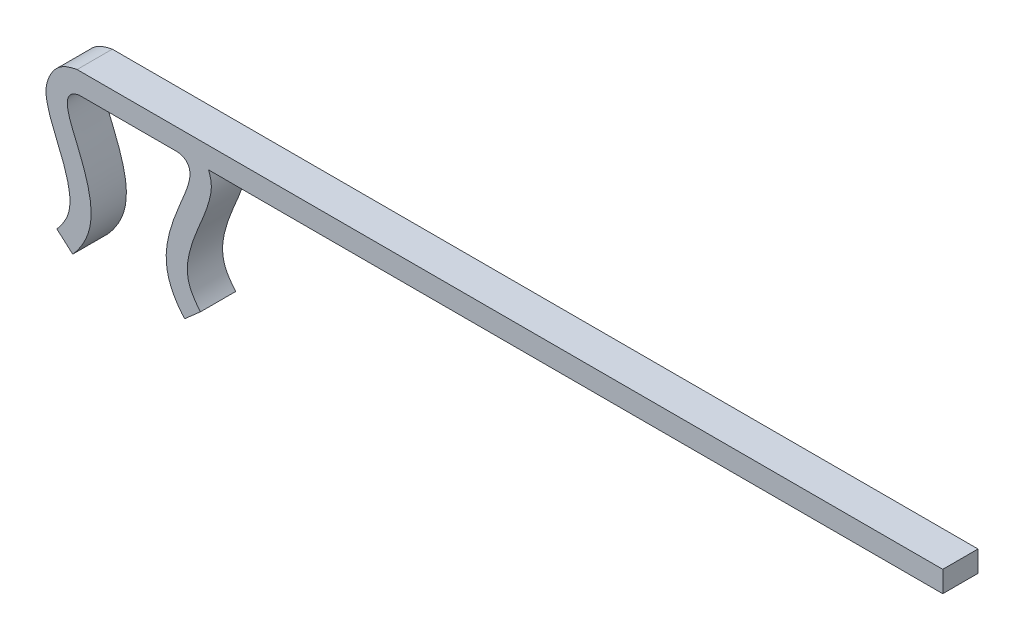
SolidWorks part; units mm, degrees
ref_plane "Front Plane" through (0, 0, 0) normal (0, 0, 1) x (1, 0, 0)
ref_plane "Top Plane" through (0, 0, 0) normal (0, 1, 0) x (1, 0, 0)
ref_plane "Right Plane" through (0, 0, 0) normal (1, 0, 0) x (0, 0, -1)
sketch "Sketch1" plane through (0, 0, 0) normal (0, 0, 1) x (1, 0, 0)
  line L0 (-3.0978, 0) -> (-0.55, 0) construction
  line L1 (-0.55, 2) -> (-0.7041, 2)
  line L2 (0, 2.8494) -> (0, -0.1797) construction
  line L3 (-0.55, 2) -> (0.55, 2)
  line L4 (0.7934, 0) -> (1.0189, 0.1979)
  line L5 (-0.55, -2) -> (0.55, -2)
  line L7 (0.55, 2) -> (0.7041, 2)
  line L8 (0.55, 2.3) -> (11.55, 2.3)
  line L9 (-0.55, 2.3) -> (-0.7319, 2.3)
  line L10 (-0.55, 2.3) -> (0.55, 2.3)
  line L11 (-0.7934, 0) -> (-1.0189, 0.1979)
  line L12 (1.133, 2) -> (11.55, 2)
  line L13 (11.55, 2.3) -> (11.55, 2)
  spline S0 degree 3 poles (-0.7041, 2) (-0.9849, 1.9476) (-0.6535, 1.2461) (-0.4405, 0.581) (-0.6577, 0.1546) (-0.7934, 0) knots 0 0 0 0 0.316391 0.760408 1 1 1 1
  spline S1 degree 1 poles (-0.7319, 2.3) (-1.0189, 0.1979) knots 0 0 1 1 construction
  spline S2 degree 3 poles (-0.7319, 2.3) (-0.7497, 2.2967) (-0.779, 2.2922) (-0.887, 2.2619) (-1.0567, 2.1715) (-1.1959, 1.8955) (-1.157, 1.6609) (-1.0749, 1.4074) (-0.9572, 1.1539) (-0.8699, 0.8996) (-0.8276, 0.6932) (-0.8349, 0.5301) (-0.8775, 0.3872) (-0.9707, 0.2527) (-1.0189, 0.1979) knots -0.010245 -0.010245 -0.010245 -0.010245 0.00554 0.021325 0.052895 0.116035 0.179176 0.242316 0.368597 0.494877 0.621158 0.747439 0.873719 1 1 1 1
  spline S3 degree 3 poles (1.133, 2) (1.1455, 1.9701) (1.1869, 1.841) (1.157, 1.6609) (1.0749, 1.4074) (0.9572, 1.1539) (0.8699, 0.8996) (0.8276, 0.6932) (0.8349, 0.5301) (0.8775, 0.3872) (0.9707, 0.2527) (1.0189, 0.1979) knots 0.096954 0.096954 0.096954 0.096954 0.116035 0.179176 0.242316 0.368597 0.494877 0.621158 0.747439 0.873719 1 1 1 1
  spline S4 degree 3 poles (0.7041, 2) (0.9849, 1.9476) (0.6535, 1.2461) (0.4405, 0.581) (0.6577, 0.1546) (0.7934, 0) knots 0 0 0 0 0.316391 0.760408 1 1 1 1
  point P14 (0, 2)
  point P16 (0, 2.3)
  dimension "D3" = 0.3
  dimension "D1" = 0.55
  dimension "D2" = 11
extrude "Boss-Extrude1" add sketch "Sketch1" along normal blind 0.5
